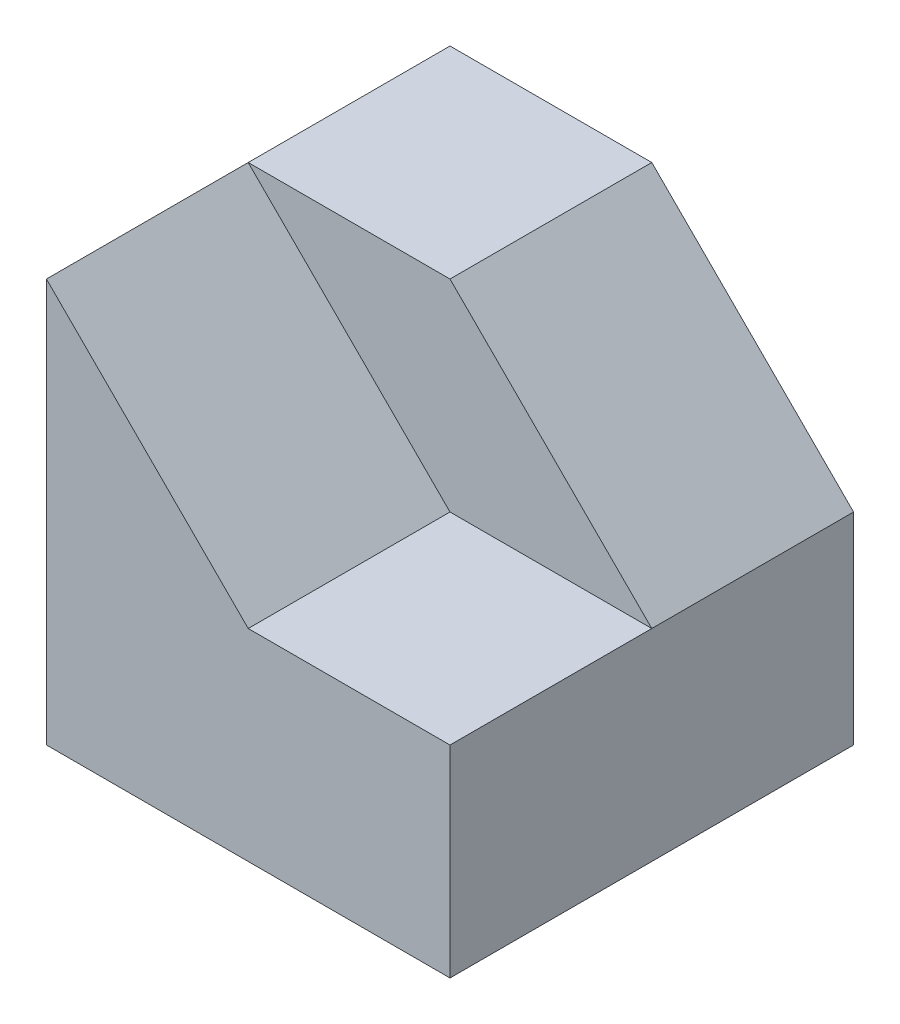
SolidWorks part; units mm, degrees
ref_plane "Alzado" through (0, 0, 0) normal (0, 0, 1) x (1, 0, 0)
ref_plane "Planta" through (0, 0, 0) normal (0, 1, 0) x (1, 0, 0)
ref_plane "Vista lateral" through (0, 0, 0) normal (1, 0, 0) x (0, 0, -1)
sketch "Croquis1" plane through (0, 0, 0) normal (0, 0, 1) x (1, 0, 0)
  line L0 (0, 0) -> (60, 0)
  line L1 (60, 0) -> (60, 60)
  line L2 (60, 60) -> (0, 60)
  line L3 (0, 60) -> (0, 0)
  dimension "D1" = 60
  dimension "D2" = 60
extrude "Saliente-Extruir1" add sketch "Croquis1" against normal blind 60
sketch "Croquis2" plane through (0, 60, 0) normal (0, 1, 0) x (1, 0, 0)
  line L0 (30, 0) -> (60, 0)
  line L1 (60, 0) -> (0, 0) construction
  line L2 (60, 0) -> (60, 30)
  line L3 (60, 60) -> (60, 0) construction
  line L4 (60, 30) -> (30, 30)
  line L5 (30, 30) -> (30, 0)
  dimension "D1" = 30
extrude "Cortar-Extruir1" cut sketch "Croquis2" against normal blind 30
sketch "Croquis3" plane through (0, 0, 0) normal (0, 0, 1) x (1, 0, 0)
  line L0 (0, 60) -> (30, 30)
  line L1 (30, 30) -> (30, 60)
  line L2 (30, 60) -> (0, 60)
extrude "Cortar-Extruir2" cut sketch "Croquis3" against normal blind 30
sketch "Croquis4" plane through (0, 0, -30) normal (0, 0, 1) x (1, 0, 0)
  line L0 (30, 60) -> (60, 30)
  line L1 (60, 60) -> (0, 60) construction
  line L2 (60, 30) -> (60, 60)
  line L3 (60, 60) -> (30, 60)
extrude "Cortar-Extruir3" cut sketch "Croquis4" against normal blind 30
